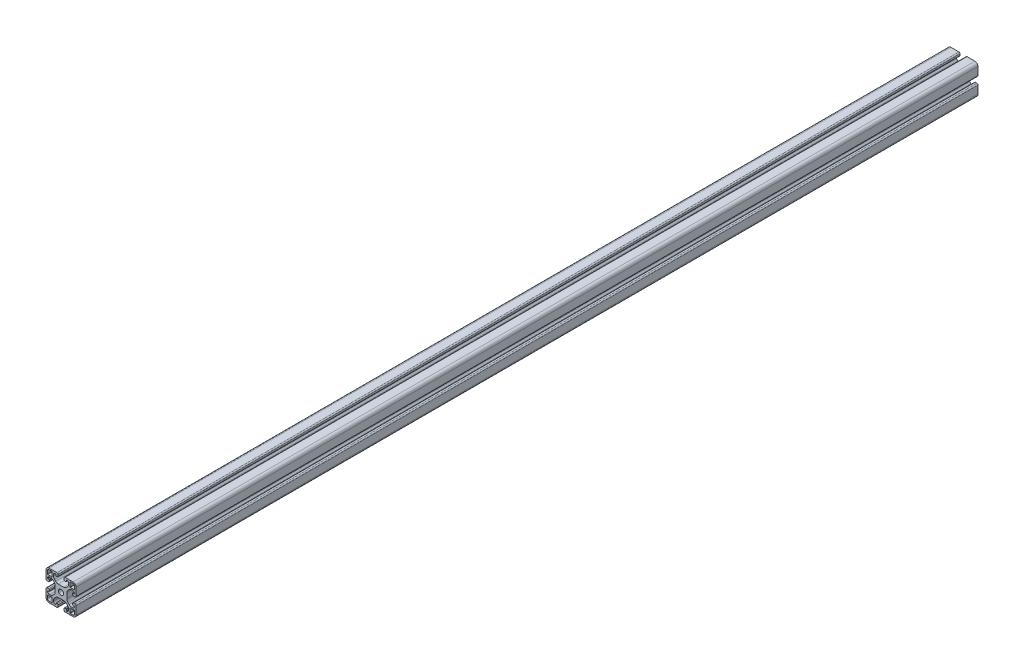
SolidWorks part; units mm, degrees
ref_plane "Plan de face" through (0, 0, 0) normal (0, 0, 1) x (1, 0, 0)
ref_plane "Plan de dessus" through (0, 0, 0) normal (0, 1, 0) x (1, 0, 0)
ref_plane "Plan de droite" through (0, 0, 0) normal (1, 0, 0) x (0, 0, -1)
ref_plane "Plan1" through (0, 0, -30) normal (0, 0, -1) x (-1, 0, 0)
sketch "Esquisse1" plane through (0, 0, -30) normal (0, 0, -1) x (-1, 0, 0)
  line B0 (-4.5, 15) -> (-4.5, 13.5)
  line B1 (-4, 13) -> (-2.5, 13)
  line B2 (-4.5, 10) -> (-5.8076, 10)
  line B3 (-9.3431, 11.4645) -> (-10.7855, 12.9069)
  line B4 (-12.25, 16.4424) -> (-12.25, 23.5576)
  line B5 (-10.7855, 27.0931) -> (-9.3431, 28.5355)
  line B6 (-5.8076, 30) -> (-4.5, 30)
  line B7 (-2.5, 27) -> (-4, 27)
  line B8 (-4.5, 26.5) -> (-4.5, 25)
  line B9 (-3.5, 24) -> (-1.5, 24)
  line B10 (0, 25.5) -> (0, 36)
  line B11 (-4, 40) -> (-14.5, 40)
  line B12 (-16, 38.5) -> (-16, 36.5)
  line B13 (-15, 35.5) -> (-13.5, 35.5)
  line B14 (-13, 36) -> (-13, 37.5)
  line B15 (-10, 35.5) -> (-10, 34.1924)
  line B16 (-11.4645, 30.6569) -> (-12.9069, 29.2145)
  line B17 (-16.4424, 27.75) -> (-23.5576, 27.75)
  line B18 (-27.0931, 29.2145) -> (-28.5355, 30.6569)
  line B19 (-30, 34.1924) -> (-30, 35.5)
  line B20 (-27, 37.5) -> (-27, 36)
  line B21 (-26.5, 35.5) -> (-25, 35.5)
  line B22 (-24, 36.5) -> (-24, 38.5)
  line B23 (-25.5, 40) -> (-36, 40)
  line B24 (-40, 36) -> (-40, 25.5)
  line B25 (-38.5, 24) -> (-36.5, 24)
  line B26 (-35.5, 25) -> (-35.5, 26.5)
  line B27 (-36, 27) -> (-37.5, 27)
  line B28 (-35.5, 30) -> (-34.1924, 30)
  line B29 (-30.6569, 28.5355) -> (-29.2145, 27.0931)
  line B30 (-27.75, 23.5576) -> (-27.75, 16.4424)
  line B31 (-29.2145, 12.9069) -> (-30.6569, 11.4645)
  line B32 (-34.1924, 10) -> (-35.5, 10)
  line B33 (-37.5, 13) -> (-36, 13)
  line B34 (-35.5, 13.5) -> (-35.5, 15)
  line B35 (-36.5, 16) -> (-38.5, 16)
  line B36 (-40, 14.5) -> (-40, 4)
  line B37 (-36, 0) -> (-25.5, 0)
  line B38 (-24, 1.5) -> (-24, 3.5)
  line B39 (-25, 4.5) -> (-26.5, 4.5)
  line B40 (-27, 4) -> (-27, 2.5)
  line B41 (-30, 4.5) -> (-30, 5.8076)
  line B42 (-28.5355, 9.3431) -> (-27.0931, 10.7855)
  line B43 (-23.5576, 12.25) -> (-16.4424, 12.25)
  line B44 (-12.9069, 10.7855) -> (-11.4645, 9.3431)
  line B45 (-10, 5.8076) -> (-10, 4.5)
  line B46 (-13, 2.5) -> (-13, 4)
  line B47 (-13.5, 4.5) -> (-15, 4.5)
  line B48 (-16, 3.5) -> (-16, 1.5)
  line B49 (-14.5, 0) -> (-4, 0)
  line B50 (0, 4) -> (0, 14.5)
  line B51 (-1.5, 16) -> (-3.5, 16)
  line B52 (-4, 1.8) -> (-7.7, 1.8)
  line B53 (-8.2, 2.3) -> (-8.2, 7.7)
  line B54 (-7.7, 8.2) -> (-2.3, 8.2)
  line B55 (-1.8, 7.7) -> (-1.8, 4)
  line B56 (-38.2, 4) -> (-38.2, 7.7)
  line B57 (-37.7, 8.2) -> (-32.3, 8.2)
  line B58 (-31.8, 7.7) -> (-31.8, 2.3)
  line B59 (-32.3, 1.8) -> (-36, 1.8)
  line B60 (-36, 38.2) -> (-32.3, 38.2)
  line B61 (-31.8, 37.7) -> (-31.8, 32.3)
  line B62 (-32.3, 31.8) -> (-37.7, 31.8)
  line B63 (-38.2, 32.3) -> (-38.2, 36)
  line B64 (-1.8, 36) -> (-1.8, 32.3)
  line B65 (-2.3, 31.8) -> (-7.7, 31.8)
  line B66 (-8.2, 32.3) -> (-8.2, 37.7)
  line B67 (-7.7, 38.2) -> (-4, 38.2)
  arc B68 (-4.5, 13.5) -> (-4, 13) centre (-4, 13.5) ccw
  arc B69 (-2.5, 13) -> (-2, 12.5) centre (-2.5, 12.5) cw
  arc B70 (-2, 12.5) -> (-4.5, 10) centre (-4.5, 12.5) cw
  arc B71 (-5.8076, 10) -> (-9.3431, 11.4645) centre (-5.8076, 15) cw
  arc B72 (-10.7855, 12.9069) -> (-12.25, 16.4424) centre (-7.25, 16.4424) cw
  arc B73 (-12.25, 23.5576) -> (-10.7855, 27.0931) centre (-7.25, 23.5576) cw
  arc B74 (-9.3431, 28.5355) -> (-5.8076, 30) centre (-5.8076, 25) cw
  arc B75 (-4.5, 30) -> (-2, 27.5) centre (-4.5, 27.5) cw
  arc B76 (-2, 27.5) -> (-2.5, 27) centre (-2.5, 27.5) cw
  arc B77 (-4, 27) -> (-4.5, 26.5) centre (-4, 26.5) ccw
  arc B78 (-4.5, 25) -> (-3.5, 24) centre (-3.5, 25) ccw
  arc B79 (-1.5, 24) -> (0, 25.5) centre (-1.5, 25.5) ccw
  arc B80 (0, 36) -> (-4, 40) centre (-4, 36) ccw
  arc B81 (-14.5, 40) -> (-16, 38.5) centre (-14.5, 38.5) ccw
  arc B82 (-16, 36.5) -> (-15, 35.5) centre (-15, 36.5) ccw
  arc B83 (-13.5, 35.5) -> (-13, 36) centre (-13.5, 36) ccw
  arc B84 (-13, 37.5) -> (-12.5, 38) centre (-12.5, 37.5) cw
  arc B85 (-12.5, 38) -> (-10, 35.5) centre (-12.5, 35.5) cw
  arc B86 (-10, 34.1924) -> (-11.4645, 30.6569) centre (-15, 34.1924) cw
  arc B87 (-12.9069, 29.2145) -> (-16.4424, 27.75) centre (-16.4424, 32.75) cw
  arc B88 (-23.5576, 27.75) -> (-27.0931, 29.2145) centre (-23.5576, 32.75) cw
  arc B89 (-28.5355, 30.6569) -> (-30, 34.1924) centre (-25, 34.1924) cw
  arc B90 (-30, 35.5) -> (-27.5, 38) centre (-27.5, 35.5) cw
  arc B91 (-27.5, 38) -> (-27, 37.5) centre (-27.5, 37.5) cw
  arc B92 (-27, 36) -> (-26.5, 35.5) centre (-26.5, 36) ccw
  arc B93 (-25, 35.5) -> (-24, 36.5) centre (-25, 36.5) ccw
  arc B94 (-24, 38.5) -> (-25.5, 40) centre (-25.5, 38.5) ccw
  arc B95 (-36, 40) -> (-40, 36) centre (-36, 36) ccw
  arc B96 (-40, 25.5) -> (-38.5, 24) centre (-38.5, 25.5) ccw
  arc B97 (-36.5, 24) -> (-35.5, 25) centre (-36.5, 25) ccw
  arc B98 (-35.5, 26.5) -> (-36, 27) centre (-36, 26.5) ccw
  arc B99 (-37.5, 27) -> (-38, 27.5) centre (-37.5, 27.5) cw
  arc B100 (-38, 27.5) -> (-35.5, 30) centre (-35.5, 27.5) cw
  arc B101 (-34.1924, 30) -> (-30.6569, 28.5355) centre (-34.1924, 25) cw
  arc B102 (-29.2145, 27.0931) -> (-27.75, 23.5576) centre (-32.75, 23.5576) cw
  arc B103 (-27.75, 16.4424) -> (-29.2145, 12.9069) centre (-32.75, 16.4424) cw
  arc B104 (-30.6569, 11.4645) -> (-34.1924, 10) centre (-34.1924, 15) cw
  arc B105 (-35.5, 10) -> (-38, 12.5) centre (-35.5, 12.5) cw
  arc B106 (-38, 12.5) -> (-37.5, 13) centre (-37.5, 12.5) cw
  arc B107 (-36, 13) -> (-35.5, 13.5) centre (-36, 13.5) ccw
  arc B108 (-35.5, 15) -> (-36.5, 16) centre (-36.5, 15) ccw
  arc B109 (-38.5, 16) -> (-40, 14.5) centre (-38.5, 14.5) ccw
  arc B110 (-40, 4) -> (-36, 0) centre (-36, 4) ccw
  arc B111 (-25.5, 0) -> (-24, 1.5) centre (-25.5, 1.5) ccw
  arc B112 (-24, 3.5) -> (-25, 4.5) centre (-25, 3.5) ccw
  arc B113 (-26.5, 4.5) -> (-27, 4) centre (-26.5, 4) ccw
  arc B114 (-27, 2.5) -> (-27.5, 2) centre (-27.5, 2.5) cw
  arc B115 (-27.5, 2) -> (-30, 4.5) centre (-27.5, 4.5) cw
  arc B116 (-30, 5.8076) -> (-28.5355, 9.3431) centre (-25, 5.8076) cw
  arc B117 (-27.0931, 10.7855) -> (-23.5576, 12.25) centre (-23.5576, 7.25) cw
  arc B118 (-16.4424, 12.25) -> (-12.9069, 10.7855) centre (-16.4424, 7.25) cw
  arc B119 (-11.4645, 9.3431) -> (-10, 5.8076) centre (-15, 5.8076) cw
  arc B120 (-10, 4.5) -> (-12.5, 2) centre (-12.5, 4.5) cw
  arc B121 (-12.5, 2) -> (-13, 2.5) centre (-12.5, 2.5) cw
  arc B122 (-13, 4) -> (-13.5, 4.5) centre (-13.5, 4) ccw
  arc B123 (-15, 4.5) -> (-16, 3.5) centre (-15, 3.5) ccw
  arc B124 (-16, 1.5) -> (-14.5, 0) centre (-14.5, 1.5) ccw
  arc B125 (-4, 0) -> (0, 4) centre (-4, 4) ccw
  arc B126 (0, 14.5) -> (-1.5, 16) centre (-1.5, 14.5) ccw
  arc B127 (-3.5, 16) -> (-4.5, 15) centre (-3.5, 15) ccw
  circle B128 centre (-20, 20) radius 3.4
  arc B129 (-1.8, 4) -> (-4, 1.8) centre (-4, 4) cw
  arc B130 (-7.7, 1.8) -> (-8.2, 2.3) centre (-7.7, 2.3) cw
  arc B131 (-8.2, 7.7) -> (-7.7, 8.2) centre (-7.7, 7.7) cw
  arc B132 (-2.3, 8.2) -> (-1.8, 7.7) centre (-2.3, 7.7) cw
  arc B133 (-36, 1.8) -> (-38.2, 4) centre (-36, 4) cw
  arc B134 (-38.2, 7.7) -> (-37.7, 8.2) centre (-37.7, 7.7) cw
  arc B135 (-32.3, 8.2) -> (-31.8, 7.7) centre (-32.3, 7.7) cw
  arc B136 (-31.8, 2.3) -> (-32.3, 1.8) centre (-32.3, 2.3) cw
  arc B137 (-38.2, 36) -> (-36, 38.2) centre (-36, 36) cw
  arc B138 (-32.3, 38.2) -> (-31.8, 37.7) centre (-32.3, 37.7) cw
  arc B139 (-31.8, 32.3) -> (-32.3, 31.8) centre (-32.3, 32.3) cw
  arc B140 (-37.7, 31.8) -> (-38.2, 32.3) centre (-37.7, 32.3) cw
  arc B141 (-4, 38.2) -> (-1.8, 36) centre (-4, 36) cw
  arc B142 (-1.8, 32.3) -> (-2.3, 31.8) centre (-2.3, 32.3) cw
  arc B143 (-7.7, 31.8) -> (-8.2, 32.3) centre (-7.7, 32.3) cw
  arc B144 (-8.2, 37.7) -> (-7.7, 38.2) centre (-7.7, 37.7) cw
sketch_block_instance "Bloc1-1"
sketch_block "Bloc1"
extrude "Boss.-Extru.1" add sketch "Esquisse1" against normal blind 1200
